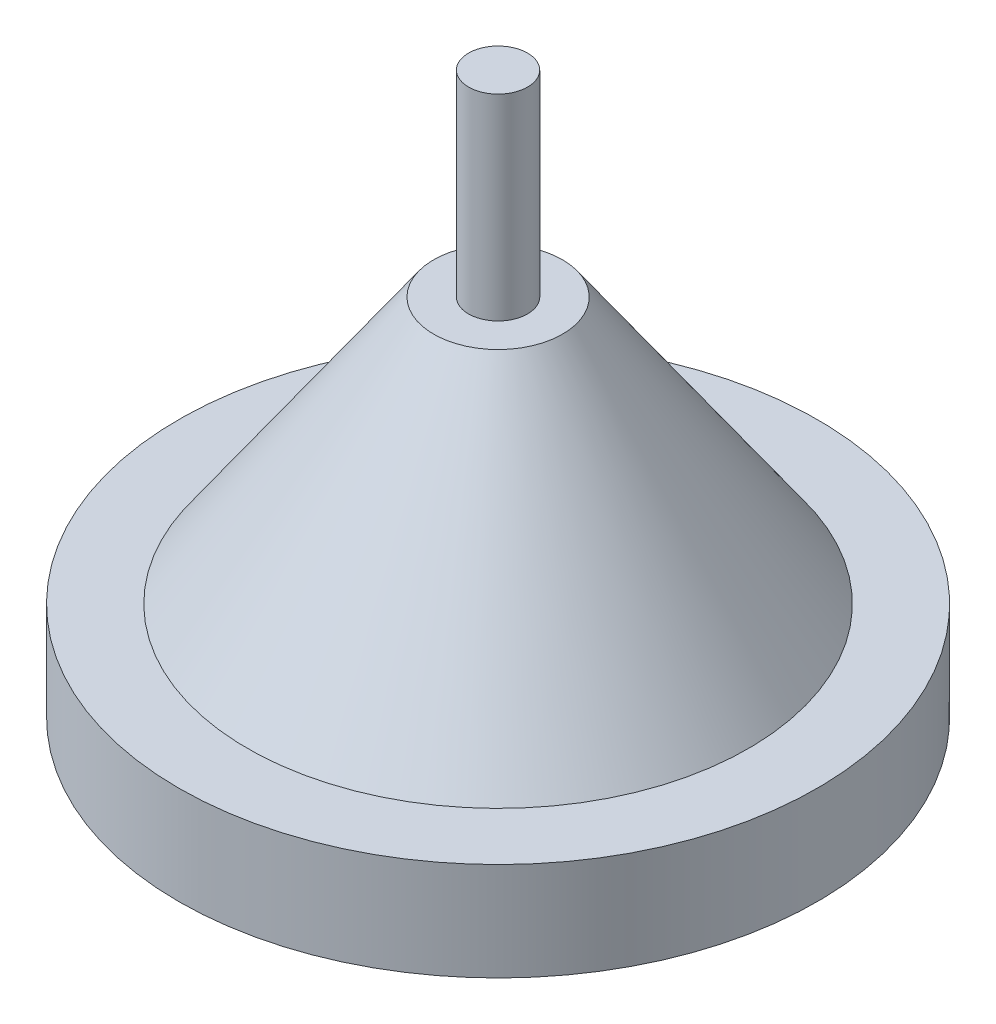
SolidWorks part; units mm, degrees
ref_plane "정면" through (0, 0, 0) normal (0, 0, 1) x (1, 0, 0)
ref_plane "윗면" through (0, 0, 0) normal (0, 1, 0) x (1, 0, 0)
ref_plane "우측면" through (0, 0, 0) normal (1, 0, 0) x (0, 0, -1)
sketch "스케치1" plane through (0, 0, 0) normal (0, 1, 0) x (1, 0, 0)
  circle A0 centre (0, 0) radius 25.5
  dimension "D1" = 51
ref_plane "평면1" through (0, 27.05, 0) normal (0, 1, 0) x (1, 0, 0)
sketch "스케치2" plane through (0, 27.05, 0) normal (0, 1, 0) x (1, 0, 0)
  circle A0 centre (0, 0) radius 6.56
  dimension "D1" = 13.12
loft "로프트1" add profiles "스케치2", "스케치1"
sketch "스케치3" plane through (0, 0, 0) normal (0, 1, 0) x (1, 0, 0)
  circle A0 centre (0, 0) radius 32.5
  dimension "D1" = 65
extrude "보스-돌출1" add sketch "스케치3" against normal blind 10 contours A0
sketch "스케치4" plane through (0, 27.05, 0) normal (0, 1, 0) x (1, 0, 0)
  circle A0 centre (0, 0) radius 3
  dimension "D1" = 6
extrude "보스-돌출2" add sketch "스케치4" along normal blind 20
